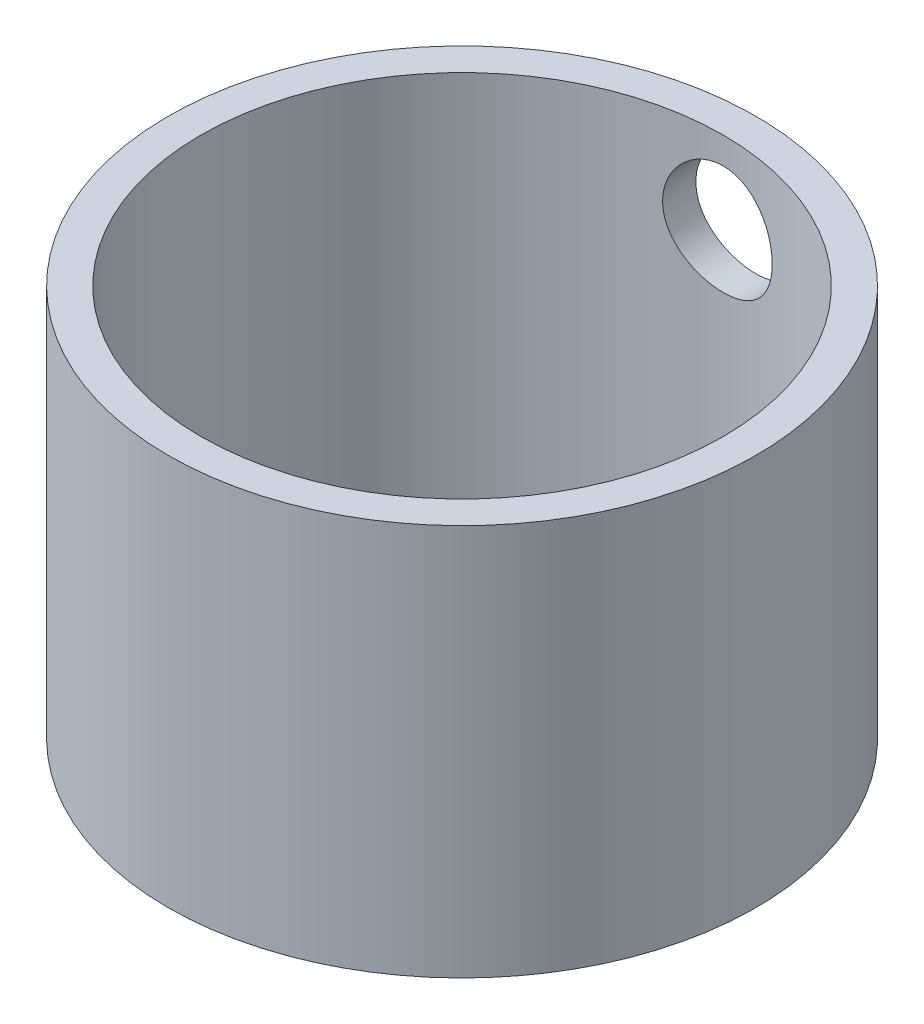
SolidWorks part; units mm, degrees
material "AISI 316 Annealed Stainless Steel Bar (SS)"
ref_plane "Front Plane" through (0, 0, 0) normal (0, 0, 1) x (1, 0, 0)
ref_plane "Top Plane" through (0, 0, 0) normal (0, 1, 0) x (1, 0, 0)
ref_plane "Right Plane" through (0, 0, 0) normal (1, 0, 0) x (0, 0, -1)
sketch "Sketch1" plane through (0, 0, 0) normal (0, 1, 0) x (1, 0, 0)
  circle A0 centre (0, 0) radius 50.8
  circle A1 centre (0, 0) radius 57.15
  dimension "D1" = 114.3
  dimension "D2" = 6.35
extrude "Boss-Extrude1" add sketch "Sketch1" along normal blind 76.2
sketch "Sketch2" plane through (0, 0, 0) normal (0, 0, 1) x (1, 0, 0)
  line L0 (0, 60.325) -> (0, 76.2) construction
  line L1 (50.8, 76.2) -> (-50.8, 76.2) construction
  circle A0 centre (0, 60.325) radius 10.668
  dimension "D1" = 21.336
  dimension "D2" = 15.875
extrude "Cut-Extrude1" cut sketch "Sketch2" against normal up to next
